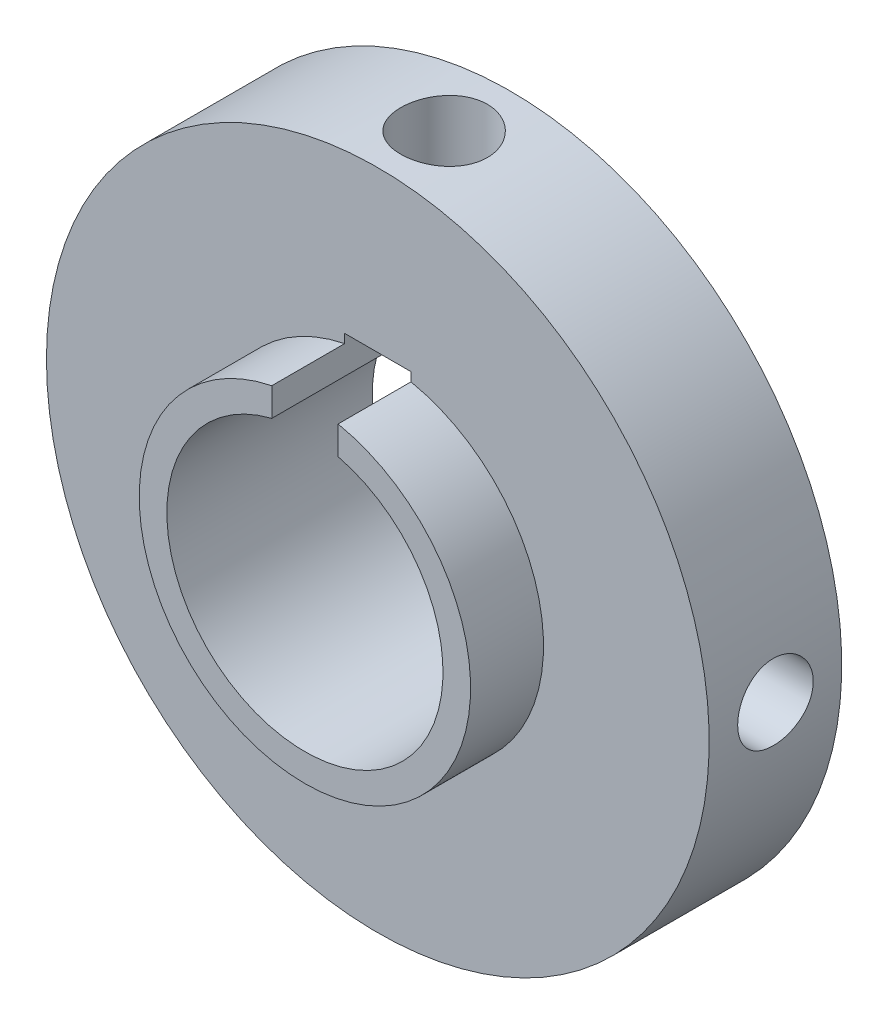
SolidWorks part; units mm, degrees
material "Plain Carbon Steel"
ref_plane "Front Plane" through (0, 0, 0) normal (0, 0, 1) x (1, 0, 0)
ref_plane "Top Plane" through (0, 0, 0) normal (0, 1, 0) x (1, 0, 0)
ref_plane "Right Plane" through (0, 0, 0) normal (1, 0, 0) x (0, 0, -1)
sketch "Sketch1" plane through (0, 0, 0) normal (0, 1, 0) x (1, 0, 0)
  line L0 (0, 72.8201) -> (0, 0) construction
  line L1 (0, 0) -> (-77.7246, 0) construction
  line L2 (7.9375, 11.811) -> (7.9375, 0)
  line L3 (7.9375, 0) -> (9.525, 0)
  line L4 (9.525, 0) -> (9.525, 4.191)
  line L5 (9.525, 4.191) -> (19.05, 4.191)
  line L6 (19.05, 4.191) -> (19.05, 11.811)
  line L7 (19.05, 11.811) -> (7.9375, 11.811)
  dimension "D1" = 7.62
  dimension "D2" = 11.811
  dimension "D3" = 38.1
  dimension "D4" = 15.875
  dimension "D5" = 19.05
revolve "Revolve1" add sketch "Sketch1" angle 360 about L0
sketch "Sketch2" plane through (0, 0, -11.811) normal (0, 0, -1) x (-1, 0, 0)
  line L0 (1.905, 9.8425) -> (1.905, 7.7055)
  line L1 (-1.905, 9.8425) -> (1.905, 9.8425)
  line L2 (-1.905, 7.7055) -> (-1.905, 9.8425)
  line L3 (0, 0) -> (0, 9.8425) construction
  circle A0 centre (0, 0) radius 7.9375 construction
  arc A1 (-1.905, 7.7055) -> (1.905, 7.7055) centre (0, 0) ccw
  dimension "D1" = 9.8425
  dimension "D2" = 3.81
extrude "Extrude1" cut sketch "Sketch2" against normal up to surface (11.811 mm away) up to face at (-9.525, 0, 0)
sketch "Sketch3" plane through (0, 0, 0) normal (0, 1, 0) x (1, 0, 0)
  circle A0 centre (0, 8.001) radius 2.4892
  dimension "D1" = 4.9784
  dimension "D2" = 8.001
extrude "Extrude2" cut sketch "Sketch3" along normal up to next
sketch "Sketch4" plane through (0, 0, 0) normal (1, 0, 0) x (0, 0, -1)
  circle A0 centre (8.001, 0) radius 2.1717
  dimension "D1" = 4.3434
  dimension "D2" = 8.001
extrude "Extrude3" cut sketch "Sketch4" along normal up to next
